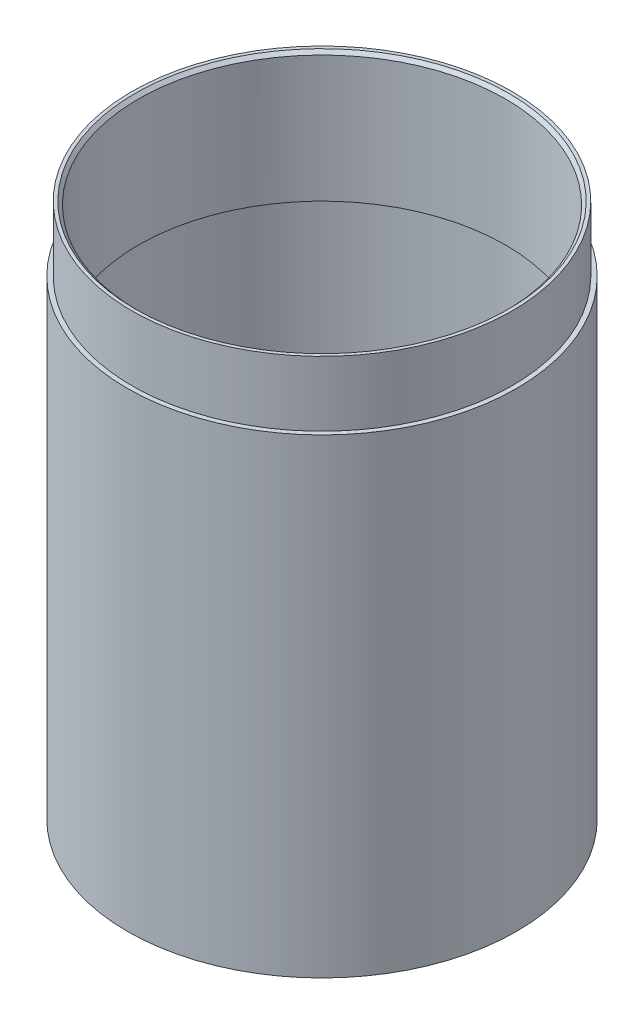
SolidWorks part; units mm, degrees
ref_plane "Front Plane" through (0, 0, 0) normal (0, 0, 1) x (1, 0, 0)
ref_plane "Top Plane" through (0, 0, 0) normal (0, 1, 0) x (1, 0, 0)
ref_plane "Right Plane" through (0, 0, 0) normal (1, 0, 0) x (0, 0, -1)
sketch "Sketch1" plane through (0, 0, 0) normal (0, 0, 1) x (1, 0, 0)
  line L0 (35.941, 30.6269) -> (35.941, 5.2269)
  line L1 (35.941, 30.6269) -> (37.211, 30.6269)
  line L2 (37.211, 30.6269) -> (37.211, 17.9269)
  line L3 (37.211, 17.9269) -> (38.1, 17.9269)
  line L4 (38.1, 17.9269) -> (38.1, -74.1481)
  line L8 (0, -31.3896) -> (0, 34.7142) construction
  line L9 (35.941, 5.2269) -> (36.703, 5.2269)
  line L10 (36.703, 5.2269) -> (36.703, -74.1481)
  line L12 (36.703, -74.1481) -> (38.1, -74.1481)
  dimension "D1" = 73.406
  dimension "D2" = 76.2
  dimension "D3" = 74.422
  dimension "D4" = 1.27
  dimension "D5" = 104.775
  dimension "D6" = 79.375
  dimension "D7" = 12.7
revolve "Revolve1" add sketch "Sketch1" angle 360 about L8
chamfer "Chamfer1" distance 0.635 angle 45 2 edges at (0, 30.6269, -35.941) (0, -74.1481, -36.703)
